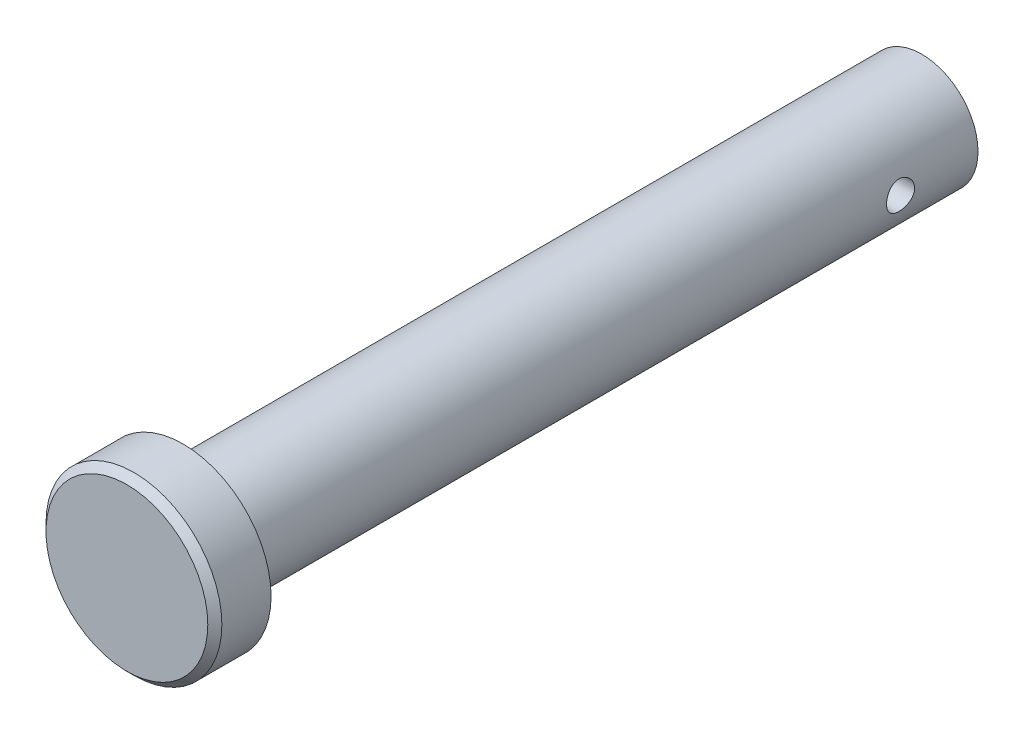
SolidWorks part; units mm, degrees
ref_plane "Front Plane" through (0, 0, 0) normal (0, 0, 1) x (1, 0, 0)
ref_plane "Top Plane" through (0, 0, 0) normal (0, 1, 0) x (1, 0, 0)
ref_plane "Right Plane" through (0, 0, 0) normal (1, 0, 0) x (0, 0, -1)
sketch "Sketch1" plane through (0, 0, 0) normal (0, 0, 1) x (1, 0, 0)
  circle A0 centre (0, 0) radius 8
  dimension "D1" = 16
extrude "Boss-Extrude1" add sketch "Sketch1" along normal blind 105
sketch "Sketch2" plane through (0, 0, 105) normal (0, 0, 1) x (1, 0, 0)
  circle A0 centre (0, 0) radius 12.5
extrude "Boss-Extrude2" add sketch "Sketch2" along normal blind 8
chamfer "Chamfer1" distance 1 angle 45 1 edges at (12.5, 0, 113)
sketch "Sketch3" plane through (0, 0, 0) normal (1, 0, 0) x (0, 0, -1)
  line L0 (-105, -12.5) -> (-105, 12.5) construction
  circle A0 centre (-11, 0) radius 2
  dimension "D1" = 4
  dimension "D2" = 94
extrude "Cut-Extrude1" cut sketch "Sketch3" against normal mid plane 1000
